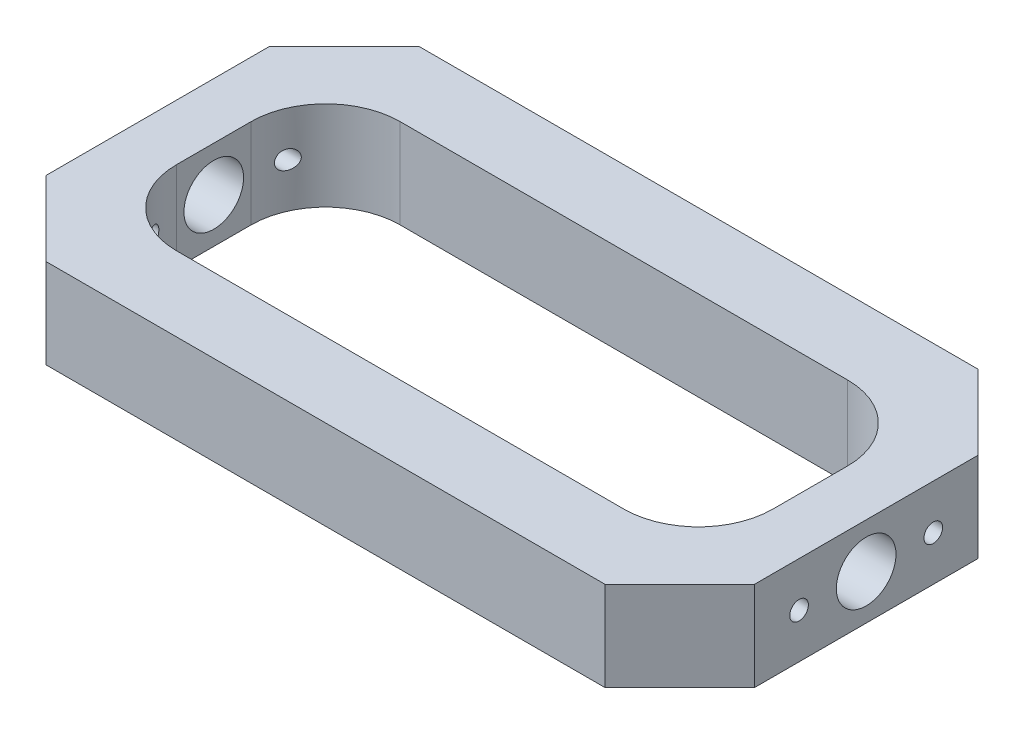
SolidWorks part; units mm, degrees
ref_plane "Front Plane" through (0, 0, 0) normal (0, 0, 1) x (1, 0, 0)
ref_plane "Top Plane" through (0, 0, 0) normal (0, 1, 0) x (1, 0, 0)
ref_plane "Right Plane" through (0, 0, 0) normal (1, 0, 0) x (0, 0, -1)
sketch "Sketch2" plane through (0, 0, 0) normal (0, 1, 0) x (1, 0, 0)
  line L1 (-47.5, -25) -> (47.5, -25)
  line L2 (-47.5, -25) -> (-47.5, 25)
  line L3 (-47.5, 25) -> (47.5, 25)
  line L4 (47.5, -25) -> (47.5, 25)
  line L5 (-47.5, -25) -> (47.5, 25) construction
  line L6 (-47.5, 25) -> (47.5, -25) construction
  line L7 (-40, -15) -> (40, -15)
  line L8 (-40, -15) -> (-40, 15)
  line L9 (-40, 15) -> (40, 15)
  line L10 (40, -15) -> (40, 15)
  line L11 (-40, -15) -> (40, 15) construction
  line L12 (-40, 15) -> (40, -15) construction
  point P0 (0, 0)
  point P6 (0, 0)
  dimension "D1" = 50
  dimension "D2" = 95
  dimension "D3" = 80
  dimension "D4" = 30
extrude "Boss-Extrude1" add sketch "Sketch2" along normal mid plane 12
sketch "Sketch4" plane through (0, 0, 0) normal (1, 0, 0) x (0, 0, -1)
  line L0 (-9, 0) -> (9, 0) construction
  line L1 (-9, 6) -> (9, 6) construction
  line L2 (-9, -6) -> (9, -6) construction
  line L3 (-15, 6) -> (15, 6) construction
  line L4 (15, 0) -> (-15, 0) construction
  circle A0 centre (0, 0) radius 4
  arc A1 (-9, 6) -> (-9, -6) centre (-9, 0) ccw construction
  arc A2 (9, -6) -> (9, 6) centre (9, 0) ccw construction
  point P5 (0, 0)
  point P10 (0, 0)
  point P15 (0, 0)
  dimension "D1" = 8
extrude "Cut-Extrude1" cut sketch "Sketch4" against normal through all both and the other way through all
fillet "Fillet1" radius 10 4 edges at (-40, 0, 15) (40, 0, 15) (40, 0, -15) (-40, 0, -15)
hole_wizard "M3x0.5 Tapped Hole1" positions "Sketch5" profile "Sketch7" tap size "M3x0.5" standard "ANSI Metric"
sketch "Sketch5" plane through (-47.5, 0, 0) normal (-1, 0, 0) x (0, 0, 1)
  point P0 (-9, 0)
  point P2 (9, 0)
  point P4 (0, 0)
  point P6 (0, 0)
sketch "Sketch7" plane through (-47.5, 0, -9) normal (0, 1, 0) x (0, 0, 1)
  line L0 (0, 0) -> (0, 8.3348)
  line L1 (0, 8.3348) -> (1.25, 8.3348)
  line L2 (1.25, 8.3348) -> (1.25, 0)
  line L5 (1.25, 0) -> (0, 0)
  line L11 (0, -6.35) -> (0, 107.95) construction
  dimension "Thru Tap Drill Dia." = 2.5
  dimension "Thru Tap Drill Depth" = 8.3348
cosmetic thread "Hole Thread1" parameters "D2"=3
cosmetic thread "Hole Thread2" parameters "D2"=3
mirror "Mirror1" about plane through (0, 0, 0) normal (1, 0, 0) of "M3x0.5 Tapped Hole1"
cosmetic thread "Hole Thread3" parameters "D2"=3
mirror "Hole Thread4"
chamfer "Chamfer1" distance 10 angle 45 4 edges at (47.5, 0, -25) (47.5, 0, 25) (-47.5, 0, 25) (-47.5, 0, -25)
